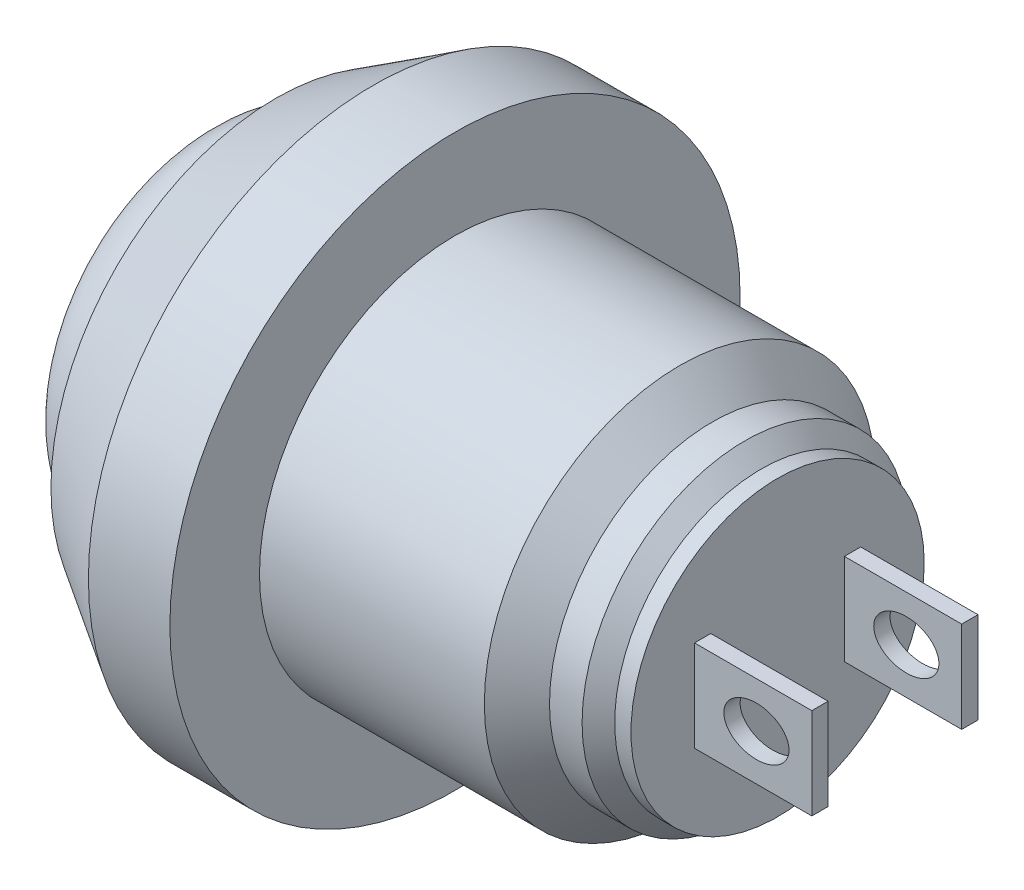
SolidWorks part; units mm, degrees
ref_plane "Front Plane" through (0, 0, 0) normal (0, 0, 1) x (1, 0, 0)
ref_plane "Top Plane" through (0, 0, 0) normal (0, 1, 0) x (1, 0, 0)
ref_plane "Right Plane" through (0, 0, 0) normal (1, 0, 0) x (0, 0, -1)
sketch "Sketch2" plane through (0, 0, 0) normal (0, 1, 0) x (1, 0, 0)
  line L0 (0, 0) -> (0, 8.75) construction
  line L1 (0, 8.75) -> (-2.5, 8.75)
  line L2 (-2.5, 8.75) -> (-5.5, 6.9)
  line L3 (-5.5, 6.9) -> (-5.5, 5.9)
  line L4 (0, 0) -> (-8.1, 0)
  line L5 (-8.1, 0) -> (-8.1, 3)
  line L6 (0, 8.75) -> (0, 6)
  line L9 (9.9, 0) -> (0, 0)
  line L10 (0, 6) -> (6.9, 6)
  line L11 (6.9, 6) -> (7.9, 5)
  line L12 (7.9, 5) -> (8.9, 5)
  line L13 (8.9, 5) -> (9.4, 4.5)
  line L14 (9.4, 4.5) -> (9.9, 4.5)
  line L15 (9.9, 4.5) -> (9.9, 0)
  line L16 (7.9, 5) -> (6.3481, 5) construction
  spline S0 degree 3 poles (-5.5, 5.9) (-6.4365, 5.9) (-8.1, 5.4944) (-8.1, 3) knots 0 0 0 0 1 1 1 1
  point P3 (0, 6)
  point P9 (0.1367, 6)
  dimension "D1" = 8.75
  dimension "D2" = 2.5
  dimension "D3" = 3
  dimension "D4" = 2.6
  dimension "D5" = 1
  dimension "D7" = 3
  dimension "D9" = 6
  dimension "D10" = 18
  dimension "D12" = 0.5
  dimension "D13" = 1
  dimension "D14" = 45
  dimension "D15" = 5
  dimension "D16" = 4.5
  dimension "D6" = 5.9
revolve "Revolve1" add sketch "Sketch2" angle 360 about L4
ref_plane "Plane1" through (0, 0, 2.3) normal (0, 0, 1) x (1, 0, 0)
sketch "Sketch3" plane through (0, 0, 2.3) normal (0, 0, 1) x (1, 0, 0)
  line L0 (9.9, -4.5) -> (9.9, 4.5) construction
  line L1 (9.9, 1.4) -> (13.5, 1.4)
  line L2 (9.9, 1.4) -> (9.9, -1.4)
  line L3 (9.9, -1.4) -> (13.5, -1.4)
  line L4 (13.5, 1.4) -> (13.5, -1.4)
  line L5 (0, 0) -> (13.5, 0) construction
  ellipse E0 centre (11.8, 0) end of major axis (12.8, 0) minor radius 0.75
  point P10 (0, 0)
  point P16 (13.5, 0)
  point P17 (12.6398, 0)
  point P18 (10.8981, 0)
  point P19 (12.8, 0)
  point P20 (10.8056, 0)
  point P21 (0, 0)
  dimension "D1" = 3.6
  dimension "D2" = 0.7
  dimension "D3" = 2
  dimension "D4" = 1.5
  dimension "D5" = 2.8
extrude "Boss-Extrude1" add sketch "Sketch3" along normal mid plane 0.5
mirror "Mirror1" about plane through (0, 0, 0) normal (0, 0, 1) of "Boss-Extrude1"
equation "\"D6@Sketch2\"=11.8/2"
